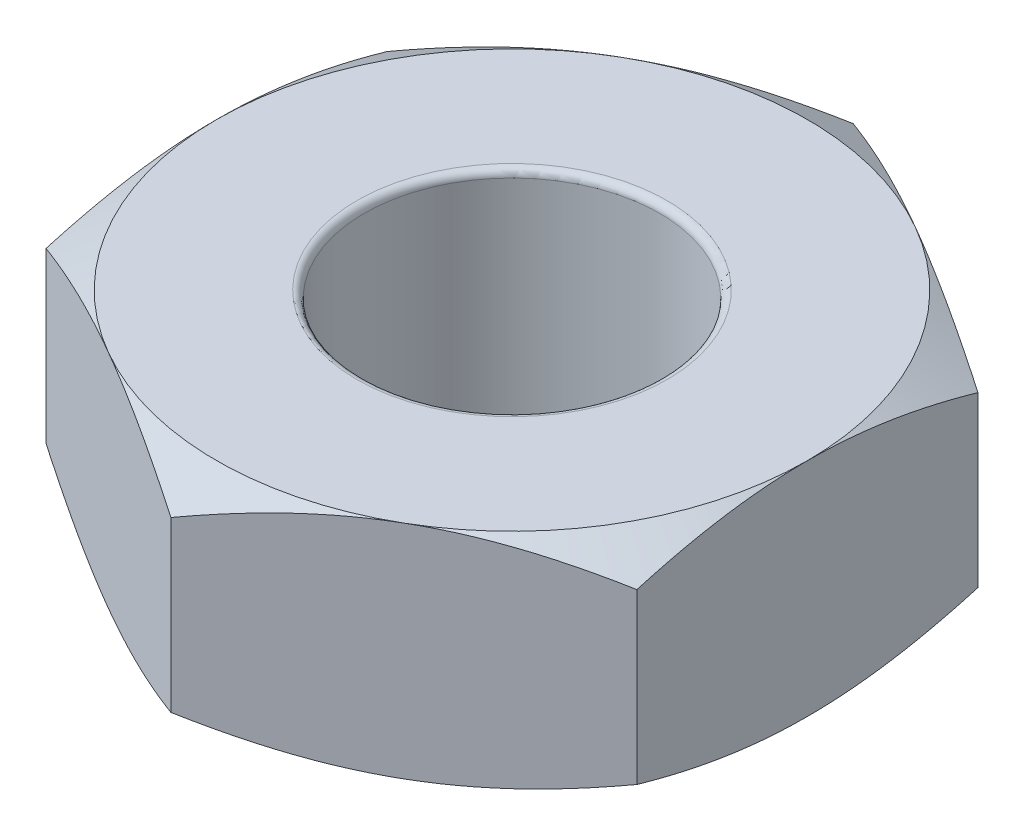
SolidWorks part; units mm, degrees
ref_plane "Front Plane" through (0, 0, 0) normal (0, 0, 1) x (1, 0, 0)
ref_plane "Top Plane" through (0, 0, 0) normal (0, 1, 0) x (1, 0, 0)
ref_plane "Right Plane" through (0, 0, 0) normal (1, 0, 0) x (0, 0, -1)
sketch "Sketch1" plane through (0, 0, 0) normal (0, 1, 0) x (1, 0, 0)
  line L1 (0, 2.3094) -> (-2, 1.1547)
  line L2 (-2, 1.1547) -> (-2, -1.1547)
  line L3 (-2, -1.1547) -> (0, -2.3094)
  line L4 (0, -2.3094) -> (2, -1.1547)
  line L5 (2, -1.1547) -> (2, 1.1547)
  line L6 (2, 1.1547) -> (0, 2.3094)
  circle A0 centre (0, 0) radius 1
  circle A1 centre (0, 0) radius 2 construction
  dimension "D1" = 2
  dimension "D2" = 4
extrude "Boss-Extrude1" add sketch "Sketch1" along normal blind 1.5
sketch "Sketch2" plane through (0, 1.5, 0) normal (0, 1, 0) x (1, 0, 0)
  circle A0 centre (0, 0) radius 2 construction
  circle A1 centre (0, 0) radius 2
extrude "Cut-Extrude1" cut sketch "Sketch2" against normal blind 2 draft 60 flip side to cut
sketch "Sketch3" plane through (0, 0, 0) normal (0, -1, 0) x (1, 0, 0)
  circle A0 centre (0, 0) radius 2 construction
  circle A1 centre (0, 0) radius 2
extrude "Cut-Extrude2" cut sketch "Sketch3" against normal blind 2 draft 60 flip side to cut
fillet "Fillet1" radius 0.05 2 edges at (0, 0, 1) (0, 1.5, 1)
